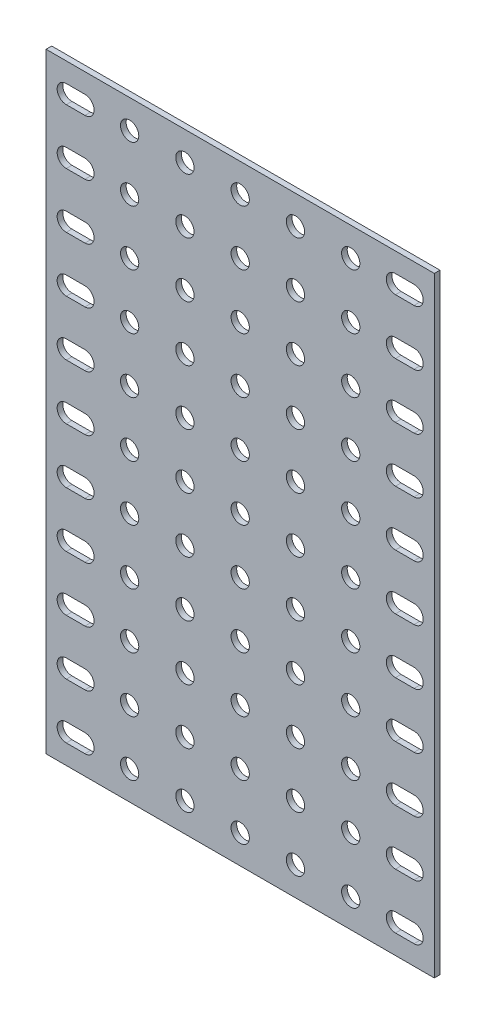
SolidWorks part; units mm, degrees
ref_plane "Front Plane" through (0, 0, 0) normal (0, 0, 1) x (1, 0, 0)
ref_plane "Top Plane" through (0, 0, 0) normal (0, 1, 0) x (1, 0, 0)
ref_plane "Right Plane" through (0, 0, 0) normal (1, 0, 0) x (0, 0, -1)
sketch "Sketch1" plane through (0, 0, 0) normal (0, 0, 1) x (1, 0, 0)
  line L0 (61.36, 0) -> (65.66, 0) construction
  line L1 (61.36, 2.11) -> (65.66, 2.11)
  line L2 (61.36, -2.11) -> (65.66, -2.11)
  line L3 (61.36, -12.76) -> (65.66, -12.76) construction
  line L4 (61.36, -10.65) -> (65.66, -10.65)
  line L5 (61.36, -14.87) -> (65.66, -14.87)
  line L6 (61.36, -25.52) -> (65.66, -25.52) construction
  line L7 (61.36, -23.41) -> (65.66, -23.41)
  line L8 (61.36, -27.63) -> (65.66, -27.63)
  line L9 (61.36, -38.28) -> (65.66, -38.28) construction
  line L10 (61.36, -36.17) -> (65.66, -36.17)
  line L11 (61.36, -40.39) -> (65.66, -40.39)
  line L12 (61.36, -51.04) -> (65.66, -51.04) construction
  line L13 (61.36, -48.93) -> (65.66, -48.93)
  line L14 (61.36, -53.15) -> (65.66, -53.15)
  line L15 (61.36, -63.8) -> (65.66, -63.8) construction
  line L16 (61.36, -61.69) -> (65.66, -61.69)
  line L17 (61.36, -65.91) -> (65.66, -65.91)
  line L18 (61.36, -76.56) -> (65.66, -76.56) construction
  line L19 (61.36, -74.45) -> (65.66, -74.45)
  line L20 (61.36, -78.67) -> (65.66, -78.67)
  line L21 (61.36, -89.32) -> (65.66, -89.32) construction
  line L22 (61.36, -87.21) -> (65.66, -87.21)
  line L23 (61.36, -91.43) -> (65.66, -91.43)
  line L24 (61.36, -102.08) -> (65.66, -102.08) construction
  line L25 (61.36, -99.97) -> (65.66, -99.97)
  line L26 (61.36, -104.19) -> (65.66, -104.19)
  line L27 (61.36, -114.84) -> (65.66, -114.84) construction
  line L28 (61.36, -112.73) -> (65.66, -112.73)
  line L29 (61.36, -116.95) -> (65.66, -116.95)
  line L30 (61.36, -127.6) -> (65.66, -127.6) construction
  line L31 (61.36, -125.49) -> (65.66, -125.49)
  line L32 (61.36, -129.71) -> (65.66, -129.71)
  line L33 (25.52, 0) -> (25.52, -127.6) construction
  line L34 (-10.32, 0) -> (-14.62, 0) construction
  line L35 (-10.32, 2.11) -> (-14.62, 2.11)
  line L36 (-10.32, -2.11) -> (-14.62, -2.11)
  line L37 (-10.32, -12.76) -> (-14.62, -12.76) construction
  line L38 (-10.32, -10.65) -> (-14.62, -10.65)
  line L39 (-10.32, -14.87) -> (-14.62, -14.87)
  line L40 (-10.32, -25.52) -> (-14.62, -25.52) construction
  line L41 (-10.32, -23.41) -> (-14.62, -23.41)
  line L42 (-10.32, -27.63) -> (-14.62, -27.63)
  line L43 (-10.32, -38.28) -> (-14.62, -38.28) construction
  line L44 (-10.32, -36.17) -> (-14.62, -36.17)
  line L45 (-10.32, -40.39) -> (-14.62, -40.39)
  line L46 (-10.32, -51.04) -> (-14.62, -51.04) construction
  line L47 (-10.32, -48.93) -> (-14.62, -48.93)
  line L48 (-10.32, -53.15) -> (-14.62, -53.15)
  line L49 (-10.32, -63.8) -> (-14.62, -63.8) construction
  line L50 (-10.32, -61.69) -> (-14.62, -61.69)
  line L51 (-10.32, -65.91) -> (-14.62, -65.91)
  line L52 (-10.32, -76.56) -> (-14.62, -76.56) construction
  line L53 (-10.32, -74.45) -> (-14.62, -74.45)
  line L54 (-10.32, -78.67) -> (-14.62, -78.67)
  line L55 (-10.32, -89.32) -> (-14.62, -89.32) construction
  line L56 (-10.32, -87.21) -> (-14.62, -87.21)
  line L57 (-10.32, -91.43) -> (-14.62, -91.43)
  line L58 (-10.32, -102.08) -> (-14.62, -102.08) construction
  line L59 (-10.32, -99.97) -> (-14.62, -99.97)
  line L60 (-10.32, -104.19) -> (-14.62, -104.19)
  line L61 (-10.32, -114.84) -> (-14.62, -114.84) construction
  line L62 (-10.32, -112.73) -> (-14.62, -112.73)
  line L63 (-10.32, -116.95) -> (-14.62, -116.95)
  line L64 (-10.32, -127.6) -> (-14.62, -127.6) construction
  line L65 (-10.32, -125.49) -> (-14.62, -125.49)
  line L66 (-10.32, -129.71) -> (-14.62, -129.71)
  line L67 (-14.62, 2.11) -> (-14.62, 6.63) construction
  line L68 (-16.73, 0) -> (-19.29, 0) construction
  line L69 (-14.62, 6.63) -> (-33.1185, 6.63) construction
  line L70 (-19.29, 0) -> (-19.29, 6.63) construction
  line L72 (-19.29, 6.63) -> (70.33, 6.63)
  line L73 (-19.29, 6.63) -> (-19.29, -134.23)
  line L74 (-19.29, -134.23) -> (70.33, -134.23)
  line L75 (70.33, 6.63) -> (70.33, -134.23)
  circle A0 centre (0, 0) radius 2.11
  circle A1 centre (12.76, 0) radius 2.11
  circle A2 centre (25.52, 0) radius 2.11
  circle A3 centre (38.28, 0) radius 2.11
  circle A4 centre (51.04, 0) radius 2.11
  circle A5 centre (12.76, -12.76) radius 2.11
  circle A6 centre (25.52, -12.76) radius 2.11
  circle A7 centre (38.28, -12.76) radius 2.11
  circle A8 centre (51.04, -12.76) radius 2.11
  circle A9 centre (12.76, -25.52) radius 2.11
  circle A10 centre (25.52, -25.52) radius 2.11
  circle A11 centre (38.28, -25.52) radius 2.11
  circle A12 centre (51.04, -25.52) radius 2.11
  circle A13 centre (12.76, -38.28) radius 2.11
  circle A14 centre (25.52, -38.28) radius 2.11
  circle A15 centre (38.28, -38.28) radius 2.11
  circle A16 centre (51.04, -38.28) radius 2.11
  circle A17 centre (12.76, -51.04) radius 2.11
  circle A18 centre (25.52, -51.04) radius 2.11
  circle A19 centre (38.28, -51.04) radius 2.11
  circle A20 centre (51.04, -51.04) radius 2.11
  circle A21 centre (12.76, -63.8) radius 2.11
  circle A22 centre (25.52, -63.8) radius 2.11
  circle A23 centre (38.28, -63.8) radius 2.11
  circle A24 centre (51.04, -63.8) radius 2.11
  circle A25 centre (12.76, -76.56) radius 2.11
  circle A26 centre (25.52, -76.56) radius 2.11
  circle A27 centre (38.28, -76.56) radius 2.11
  circle A28 centre (51.04, -76.56) radius 2.11
  circle A29 centre (12.76, -89.32) radius 2.11
  circle A30 centre (25.52, -89.32) radius 2.11
  circle A31 centre (38.28, -89.32) radius 2.11
  circle A32 centre (51.04, -89.32) radius 2.11
  circle A33 centre (12.76, -102.08) radius 2.11
  circle A34 centre (25.52, -102.08) radius 2.11
  circle A35 centre (38.28, -102.08) radius 2.11
  circle A36 centre (51.04, -102.08) radius 2.11
  circle A37 centre (12.76, -114.84) radius 2.11
  circle A38 centre (25.52, -114.84) radius 2.11
  circle A39 centre (38.28, -114.84) radius 2.11
  circle A40 centre (51.04, -114.84) radius 2.11
  circle A41 centre (12.76, -127.6) radius 2.11
  circle A42 centre (25.52, -127.6) radius 2.11
  circle A43 centre (38.28, -127.6) radius 2.11
  circle A44 centre (51.04, -127.6) radius 2.11
  circle A45 centre (0, -12.76) radius 2.11
  circle A46 centre (0, -25.52) radius 2.11
  circle A47 centre (0, -38.28) radius 2.11
  circle A48 centre (0, -51.04) radius 2.11
  circle A49 centre (0, -63.8) radius 2.11
  circle A50 centre (0, -76.56) radius 2.11
  circle A51 centre (0, -89.32) radius 2.11
  circle A52 centre (0, -102.08) radius 2.11
  circle A53 centre (0, -114.84) radius 2.11
  circle A54 centre (0, -127.6) radius 2.11
  arc A55 (61.36, 2.11) -> (61.36, -2.11) centre (61.36, 0) ccw
  arc A56 (65.66, -2.11) -> (65.66, 2.11) centre (65.66, 0) ccw
  arc A57 (61.36, -10.65) -> (61.36, -14.87) centre (61.36, -12.76) ccw
  arc A58 (65.66, -14.87) -> (65.66, -10.65) centre (65.66, -12.76) ccw
  arc A59 (61.36, -23.41) -> (61.36, -27.63) centre (61.36, -25.52) ccw
  arc A60 (65.66, -27.63) -> (65.66, -23.41) centre (65.66, -25.52) ccw
  arc A61 (61.36, -36.17) -> (61.36, -40.39) centre (61.36, -38.28) ccw
  arc A62 (65.66, -40.39) -> (65.66, -36.17) centre (65.66, -38.28) ccw
  arc A63 (61.36, -48.93) -> (61.36, -53.15) centre (61.36, -51.04) ccw
  arc A64 (65.66, -53.15) -> (65.66, -48.93) centre (65.66, -51.04) ccw
  arc A65 (61.36, -61.69) -> (61.36, -65.91) centre (61.36, -63.8) ccw
  arc A66 (65.66, -65.91) -> (65.66, -61.69) centre (65.66, -63.8) ccw
  arc A67 (61.36, -74.45) -> (61.36, -78.67) centre (61.36, -76.56) ccw
  arc A68 (65.66, -78.67) -> (65.66, -74.45) centre (65.66, -76.56) ccw
  arc A69 (61.36, -87.21) -> (61.36, -91.43) centre (61.36, -89.32) ccw
  arc A70 (65.66, -91.43) -> (65.66, -87.21) centre (65.66, -89.32) ccw
  arc A71 (61.36, -99.97) -> (61.36, -104.19) centre (61.36, -102.08) ccw
  arc A72 (65.66, -104.19) -> (65.66, -99.97) centre (65.66, -102.08) ccw
  arc A73 (61.36, -112.73) -> (61.36, -116.95) centre (61.36, -114.84) ccw
  arc A74 (65.66, -116.95) -> (65.66, -112.73) centre (65.66, -114.84) ccw
  arc A75 (61.36, -125.49) -> (61.36, -129.71) centre (61.36, -127.6) ccw
  arc A76 (65.66, -129.71) -> (65.66, -125.49) centre (65.66, -127.6) ccw
  arc A77 (-10.32, 2.11) -> (-10.32, -2.11) centre (-10.32, 0) cw
  arc A78 (-14.62, -2.11) -> (-14.62, 2.11) centre (-14.62, 0) cw
  arc A79 (-10.32, -10.65) -> (-10.32, -14.87) centre (-10.32, -12.76) cw
  arc A80 (-14.62, -14.87) -> (-14.62, -10.65) centre (-14.62, -12.76) cw
  arc A81 (-10.32, -23.41) -> (-10.32, -27.63) centre (-10.32, -25.52) cw
  arc A82 (-14.62, -27.63) -> (-14.62, -23.41) centre (-14.62, -25.52) cw
  arc A83 (-10.32, -36.17) -> (-10.32, -40.39) centre (-10.32, -38.28) cw
  arc A84 (-14.62, -40.39) -> (-14.62, -36.17) centre (-14.62, -38.28) cw
  arc A85 (-10.32, -48.93) -> (-10.32, -53.15) centre (-10.32, -51.04) cw
  arc A86 (-14.62, -53.15) -> (-14.62, -48.93) centre (-14.62, -51.04) cw
  arc A87 (-10.32, -61.69) -> (-10.32, -65.91) centre (-10.32, -63.8) cw
  arc A88 (-14.62, -65.91) -> (-14.62, -61.69) centre (-14.62, -63.8) cw
  arc A89 (-10.32, -74.45) -> (-10.32, -78.67) centre (-10.32, -76.56) cw
  arc A90 (-14.62, -78.67) -> (-14.62, -74.45) centre (-14.62, -76.56) cw
  arc A91 (-10.32, -87.21) -> (-10.32, -91.43) centre (-10.32, -89.32) cw
  arc A92 (-14.62, -91.43) -> (-14.62, -87.21) centre (-14.62, -89.32) cw
  arc A93 (-10.32, -99.97) -> (-10.32, -104.19) centre (-10.32, -102.08) cw
  arc A94 (-14.62, -104.19) -> (-14.62, -99.97) centre (-14.62, -102.08) cw
  arc A95 (-10.32, -112.73) -> (-10.32, -116.95) centre (-10.32, -114.84) cw
  arc A96 (-14.62, -116.95) -> (-14.62, -112.73) centre (-14.62, -114.84) cw
  arc A97 (-10.32, -125.49) -> (-10.32, -129.71) centre (-10.32, -127.6) cw
  arc A98 (-14.62, -129.71) -> (-14.62, -125.49) centre (-14.62, -127.6) cw
  point P2 (2.11, 0)
  point P4 (10.65, 0)
  point P5 (0, -2.11)
  point P114 (0, -10.65)
  point P115 (63.51, 0)
  point P122 (59.25, 0)
  point P123 (53.15, 0)
  point P124 (67.77, 0)
  point P125 (63.51, -12.76)
  point P133 (63.51, -25.52)
  point P140 (63.51, -38.28)
  point P147 (63.51, -51.04)
  point P154 (63.51, -63.8)
  point P161 (63.51, -76.56)
  point P168 (63.51, -89.32)
  point P175 (63.51, -102.08)
  point P182 (63.51, -114.84)
  point P189 (63.51, -127.6)
  point P197 (-12.47, 0)
  point P204 (-12.47, -12.76)
  point P211 (-12.47, -25.52)
  point P218 (-12.47, -38.28)
  point P225 (-12.47, -51.04)
  point P232 (-12.47, -63.8)
  point P239 (-12.47, -76.56)
  point P246 (-12.47, -89.32)
  point P253 (-12.47, -102.08)
  point P260 (-12.47, -114.84)
  point P267 (-12.47, -127.6)
  point P272 (-16.73, 0)
  point P273 (-8.21, 0)
  point P283 (67.77, -127.6)
  dimension "D1" = 4.22
  dimension "D4" = 8.54
  dimension "D5" = 8.54
  dimension "D6" = 6.1
  dimension "D7" = 8.52
  dimension "D8" = 4.22
  dimension "D10" = 8.54
  dimension "D11" = 2.56
  dimension "D12" = 4.52
  dimension "D13" = 4.52
  dimension "D14" = 2.56
  dimension "D2" = 5
  dimension "D3" = 11
  dimension "D9" = 11
extrude "Boss-Extrude1" add sketch "Sketch1" along normal blind 1.3
